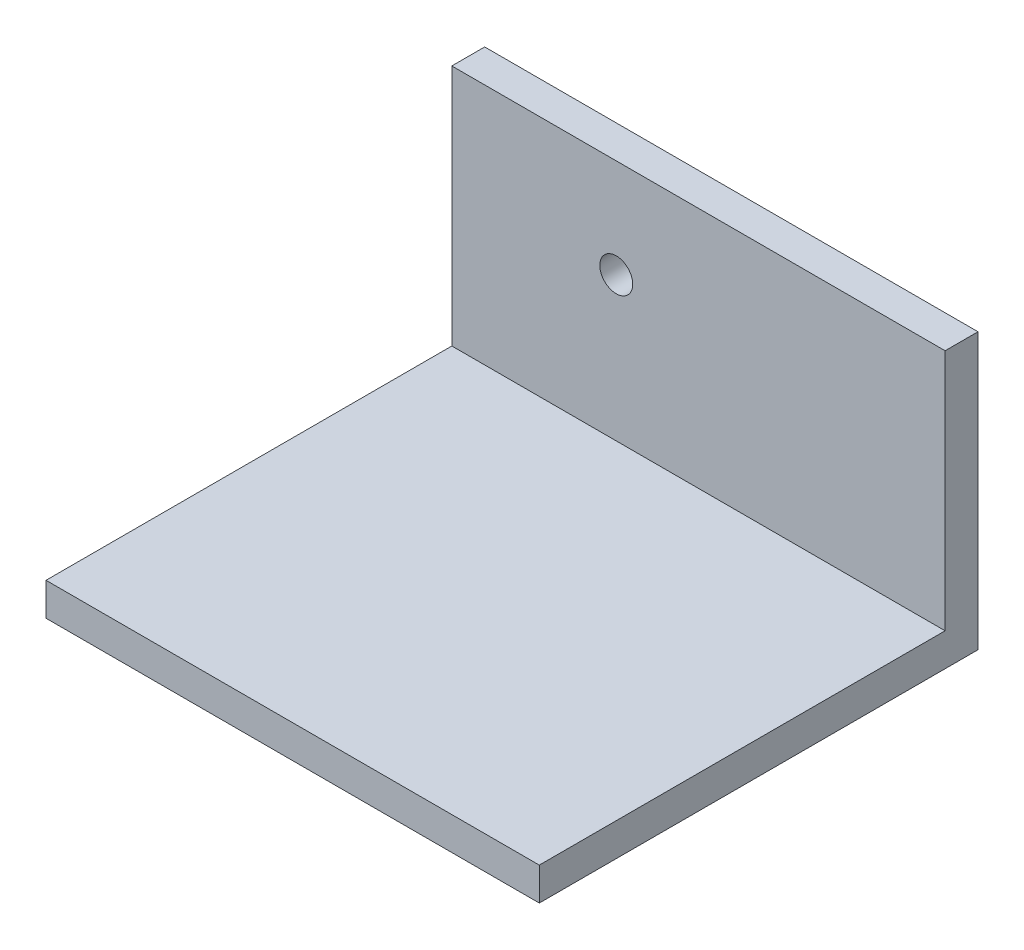
SolidWorks part; units mm, degrees
ref_plane "Front Plane" through (0, 0, 0) normal (0, 0, 1) x (1, 0, 0)
ref_plane "Top Plane" through (0, 0, 0) normal (0, 1, 0) x (1, 0, 0)
ref_plane "Right Plane" through (0, 0, 0) normal (1, 0, 0) x (0, 0, -1)
ref_plane "PL_Horn_Plate_base" through (0, 0, 3) normal (0, 0, 1) x (1, 0, 0)
sketch "SK_Horn_Plate" plane through (0, 0, 3) normal (0, 0, 1) x (1, 0, 0)
  line L0 (-20, -21.5) -> (40, -21.5)
  line L1 (40, -21.5) -> (40, 12)
  line L2 (40, 12) -> (-20, 12)
  line L3 (-20, 12) -> (-20, -21.5)
  circle A0 centre (0, 0) radius 2
  dimension "D9_SK_Horn_Plate" = 4
  dimension "P1" = 20
  dimension "P2" = 21.5
  dimension "P3" = 40
  dimension "P4" = 21.5
  dimension "P5" = 40
  dimension "P6" = 12
  dimension "P7" = 20
  dimension "P8" = 12
extrude "Horn_Plate" add sketch "SK_Horn_Plate" along normal blind 4
ref_plane "PL_Servo_Plate_base" through (0, -21.5, 0) normal (0, 1, 0) x (1, 0, 0)
sketch "SK_Servo_Plate" plane through (0, -21.5, 0) normal (0, 1, 0) x (1, 0, 0)
  line L0 (-20, -3) -> (40, -3)
  line L1 (40, -3) -> (40, -56.36)
  line L2 (40, -56.36) -> (-20, -56.36)
  line L3 (-20, -56.36) -> (-20, -3)
  dimension "P1" = 20
  dimension "P2" = 3
  dimension "P3" = 40
  dimension "P4" = 3
  dimension "P5" = 40
  dimension "P6" = 56.36
  dimension "P7" = 20
  dimension "P8" = 56.36
extrude "Servo_Plate" add sketch "SK_Servo_Plate" along normal blind 4
